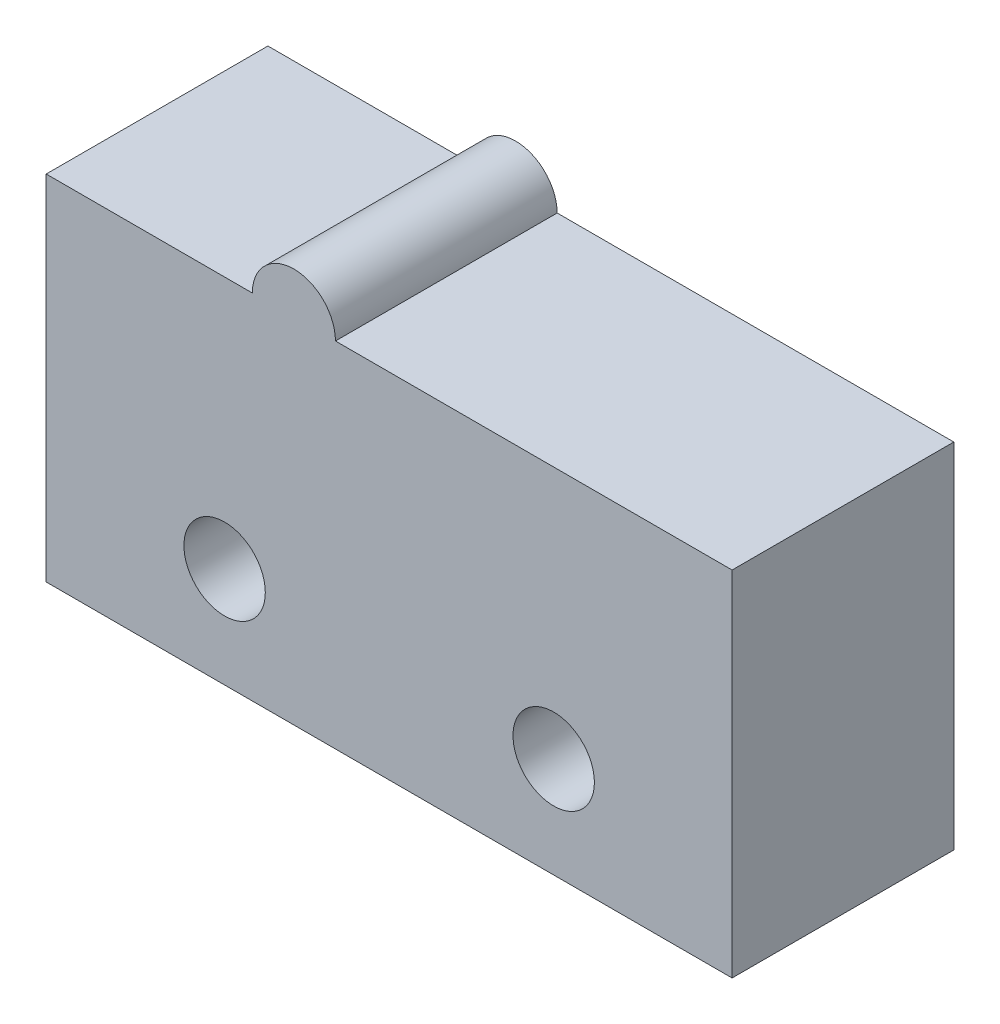
SolidWorks part; units mm, degrees
ref_plane "Front Plane" through (0, 0, 0) normal (0, 0, 1) x (1, 0, 0)
ref_plane "Top Plane" through (0, 0, 0) normal (0, 1, 0) x (1, 0, 0)
ref_plane "Right Plane" through (0, 0, 0) normal (1, 0, 0) x (0, 0, -1)
sketch "Sketch1" plane through (0, 0, 0) normal (0, 0, 1) x (1, 0, 0)
  line L0 (0, 0) -> (19.8, 0)
  line L1 (19.8, 0) -> (19.8, 10.2)
  line L2 (19.8, 10.2) -> (8.35, 10.2)
  line L3 (5.95, 10.2) -> (0, 10.2)
  line L4 (0, 10.2) -> (0, 0)
  line L5 (5.15, 2.9) -> (14.65, 2.9) construction
  line L6 (9.9, 0) -> (9.9, 10.2) construction
  arc A0 (8.35, 10.2) -> (5.95, 10.2) centre (7.15, 10.2) ccw
  circle A1 centre (14.65, 2.9) radius 1.175
  circle A2 centre (5.15, 2.9) radius 1.175
  point P14 (9.9, 2.9)
  point P15 (7.15, 11.4)
  point P16 (0, 0)
  point P17 (0, 0)
  point P18 (0, 0)
  point P19 (0, 0)
  point P20 (0, 0)
  dimension "D1" = 19.8
  dimension "D3" = 2.9
  dimension "D5" = 2.35
  dimension "D2" = 10.2
  dimension "D4" = 9.5
  dimension "D6" = 8.5
  dimension "D7" = 7.5
extrude "Boss-Extrude1" add sketch "Sketch1" along normal blind 6.4
